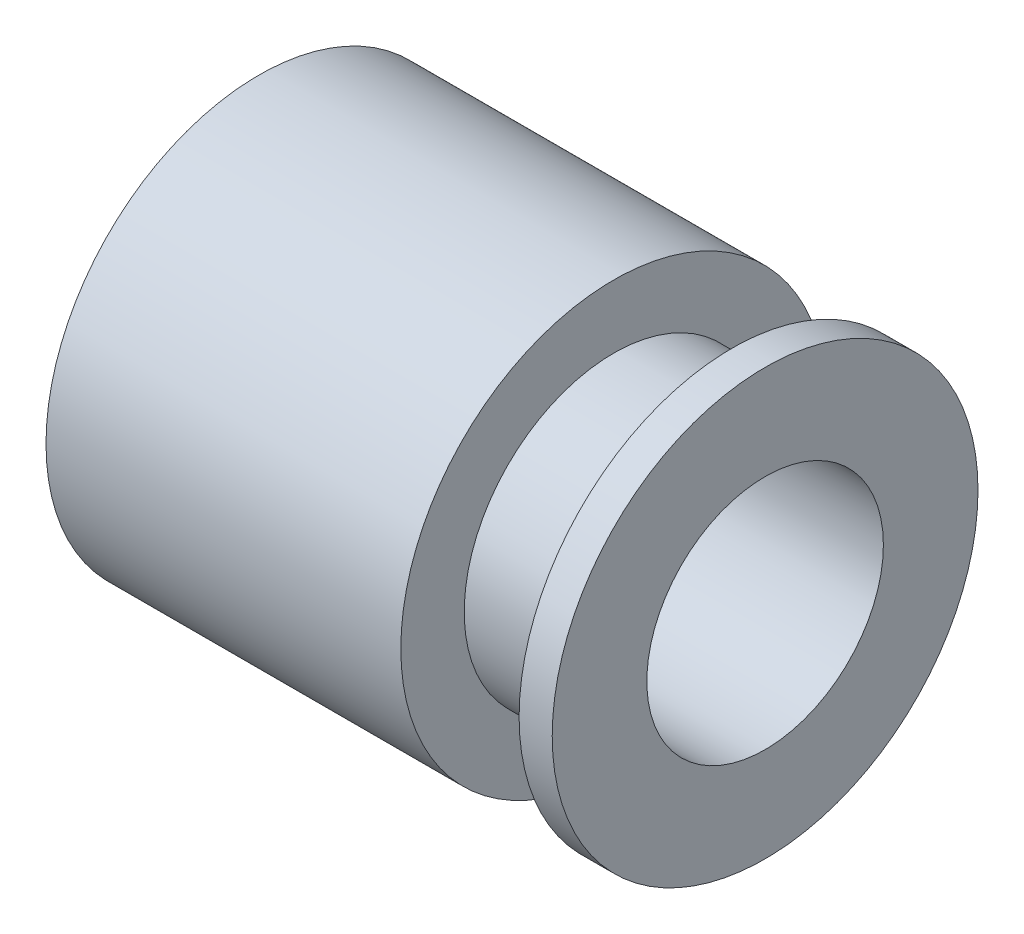
SolidWorks part; units mm, degrees
material "6061 Alloy"
ref_plane "Front Plane" through (0, 0, 0) normal (0, 0, 1) x (1, 0, 0)
ref_plane "Top Plane" through (0, 0, 0) normal (0, 1, 0) x (1, 0, 0)
ref_plane "Right Plane" through (0, 0, 0) normal (1, 0, 0) x (0, 0, -1)
sketch "Sketch1" plane through (0, 0, 0) normal (1, 0, 0) x (0, 0, -1)
  circle A0 centre (0, 0) radius 5.715
  dimension "D1" = 11.43
extrude "Boss-Extrude1" add sketch "Sketch1" along normal blind 9.525
sketch "Sketch2" plane through (9.525, 0, 0) normal (1, 0, 0) x (0, 0, -1)
  circle A0 centre (0, 0) radius 4.0132
  dimension "D1" = 8.0264
extrude "Boss-Extrude2" add sketch "Sketch2" along normal blind 3.175
sketch "Sketch3" plane through (12.7, 0, 0) normal (1, 0, 0) x (0, 0, -1)
  circle A0 centre (0, 0) radius 5.715
  dimension "D1" = 11.43
extrude "Boss-Extrude3" add sketch "Sketch3" along normal blind 0.889
sketch "Sketch4" plane through (13.589, 0, 0) normal (1, 0, 0) x (0, 0, -1)
  circle A0 centre (0, 0) radius 3.175
  dimension "D1" = 6.35
extrude "Cut-Extrude1" cut sketch "Sketch4" against normal through all
sketch "Sketch5" plane through (0, 0, 0) normal (-1, 0, 0) x (0, 0, 1)
  circle A0 centre (0, 0) radius 4.0386
  dimension "D1" = 8.0772
extrude "Cut-Extrude2" cut sketch "Sketch5" against normal blind 8.255
